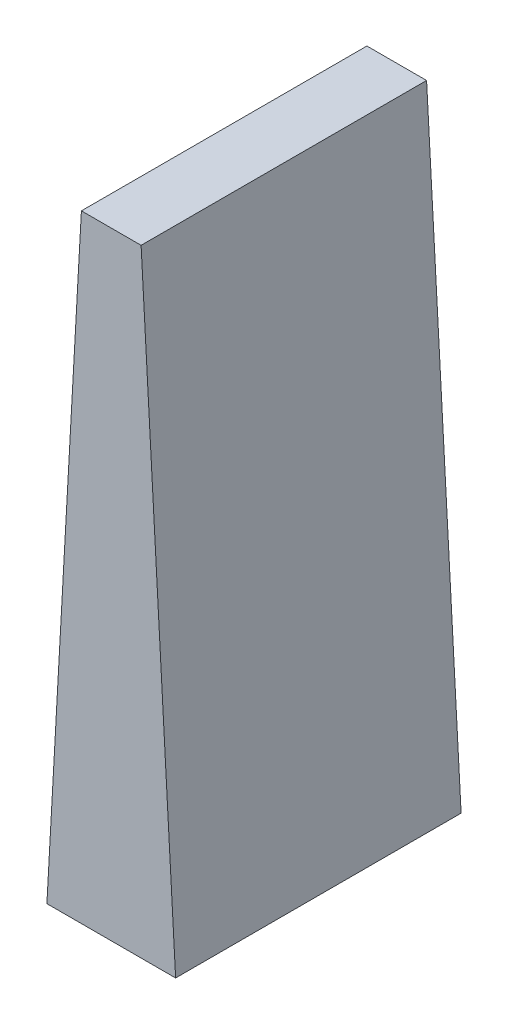
SolidWorks part; units mm, degrees
ref_plane "Front Plane" through (0, 0, 0) normal (0, 0, 1) x (1, 0, 0)
ref_plane "Top Plane" through (0, 0, 0) normal (0, 1, 0) x (1, 0, 0)
ref_plane "Right Plane" through (0, 0, 0) normal (1, 0, 0) x (0, 0, -1)
sketch "Sketch1" plane through (0, 0, 0) normal (0, 0, 1) x (1, 0, 0)
  line L0 (-2.013, -9.652) -> (-0.9335, 9.652)
  line L1 (2.0129, -9.652) -> (-2.013, -9.652)
  line L2 (2.0129, -9.652) -> (2.0129, 9.652)
  line L3 (2.0129, 9.652) -> (-2.013, 9.652)
  line L4 (-2.013, -9.652) -> (-2.013, 9.652)
  line L5 (2.0129, -9.652) -> (-2.013, 9.652) construction
  line L6 (2.0129, 9.652) -> (-2.013, -9.652) construction
  line L7 (2.0129, -9.652) -> (0.9334, 9.652)
  point P0 (0, 0)
  dimension "D1" = 1.8669
  dimension "D2" = 4.0259
  dimension "D3" = 19.304
extrude "Boss-Extrude1" add sketch "Sketch1" along normal blind 8.9281 contours L1 L7 L3 L0
